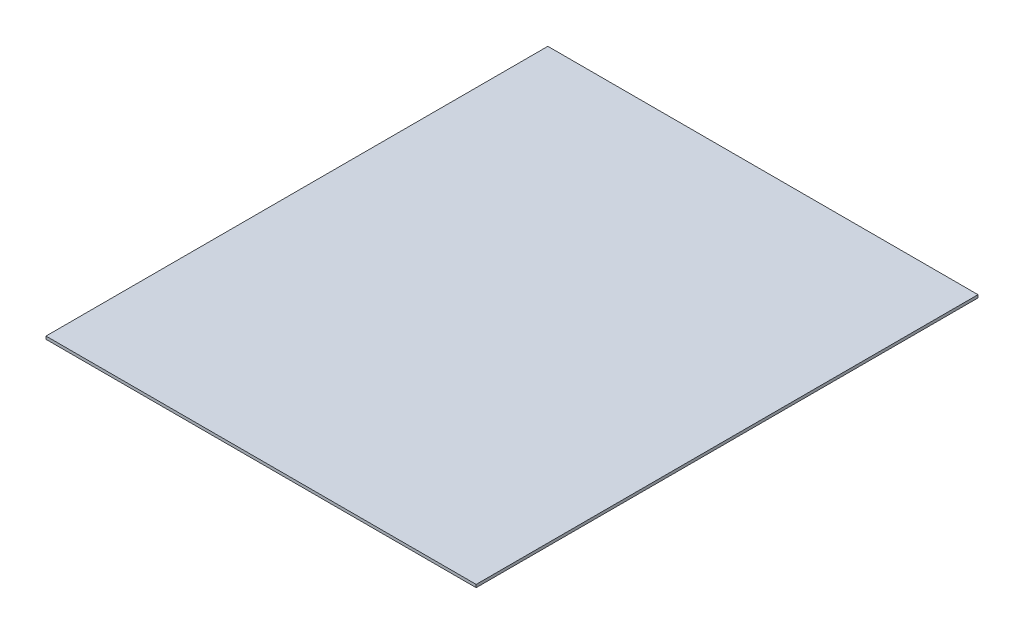
SolidWorks part; units mm, degrees
material "Verre"
ref_plane "Plan de face" through (0, 0, 0) normal (0, 0, 1) x (1, 0, 0)
ref_plane "Plan de dessus" through (0, 0, 0) normal (0, 1, 0) x (1, 0, 0)
ref_plane "Plan de droite" through (0, 0, 0) normal (1, 0, 0) x (0, 0, -1)
sketch "Esquisse1" plane through (0, 0, 0) normal (0, 1, 0) x (1, 0, 0)
  line L1 (0, 0) -> (-300, 0)
  line L2 (0, 0) -> (0, 350)
  line L3 (0, 350) -> (-300, 350)
  line L4 (-300, 0) -> (-300, 350)
  dimension "D1" = 300
  dimension "D2" = 350
extrude "Boss.-Extru.1" add sketch "Esquisse1" along normal blind 2
